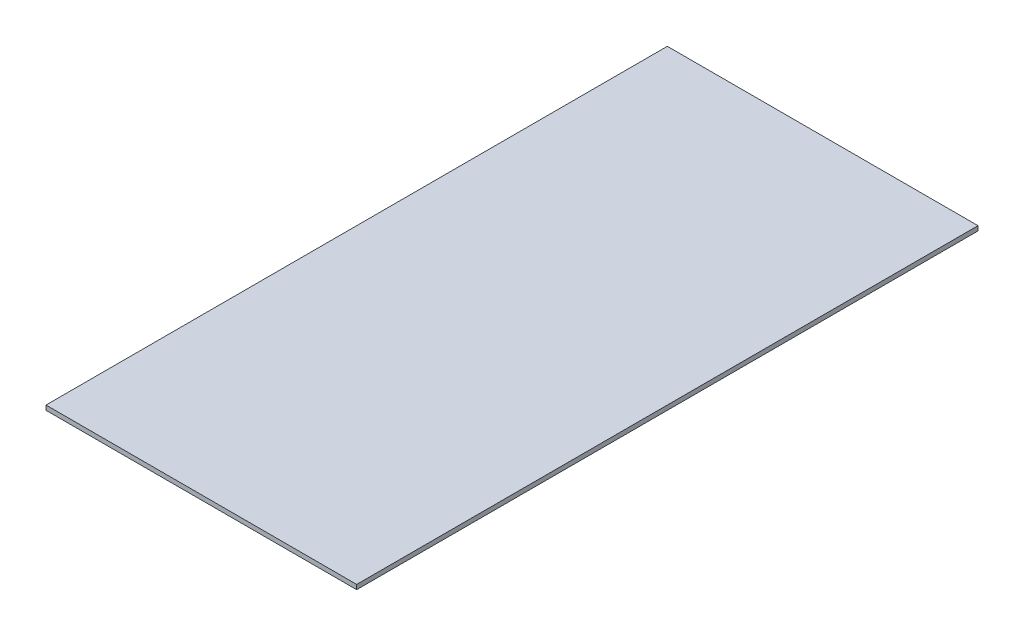
SolidWorks part; units mm, degrees
material "Poplar plywood painted"
ref_plane "Front Plane" through (0, 0, 0) normal (0, 0, 1) x (1, 0, 0)
ref_plane "Top Plane" through (0, 0, 0) normal (0, 1, 0) x (1, 0, 0)
ref_plane "Right Plane" through (0, 0, 0) normal (1, 0, 0) x (0, 0, -1)
sketch "Sketch1" plane through (0, 0, 0) normal (0, 1, 0) x (1, 0, 0)
  line L0 (-305, 610) -> (305, -610) construction
  line L1 (-305, 610) -> (305, 610)
  line L2 (-305, 610) -> (-305, -610)
  line L3 (-305, -610) -> (305, -610)
  line L4 (305, 610) -> (305, -610)
  dimension "D1" = 610
  dimension "D2" = 1220
extrude "Boss-Extrude1" add sketch "Sketch1" along normal blind 9
